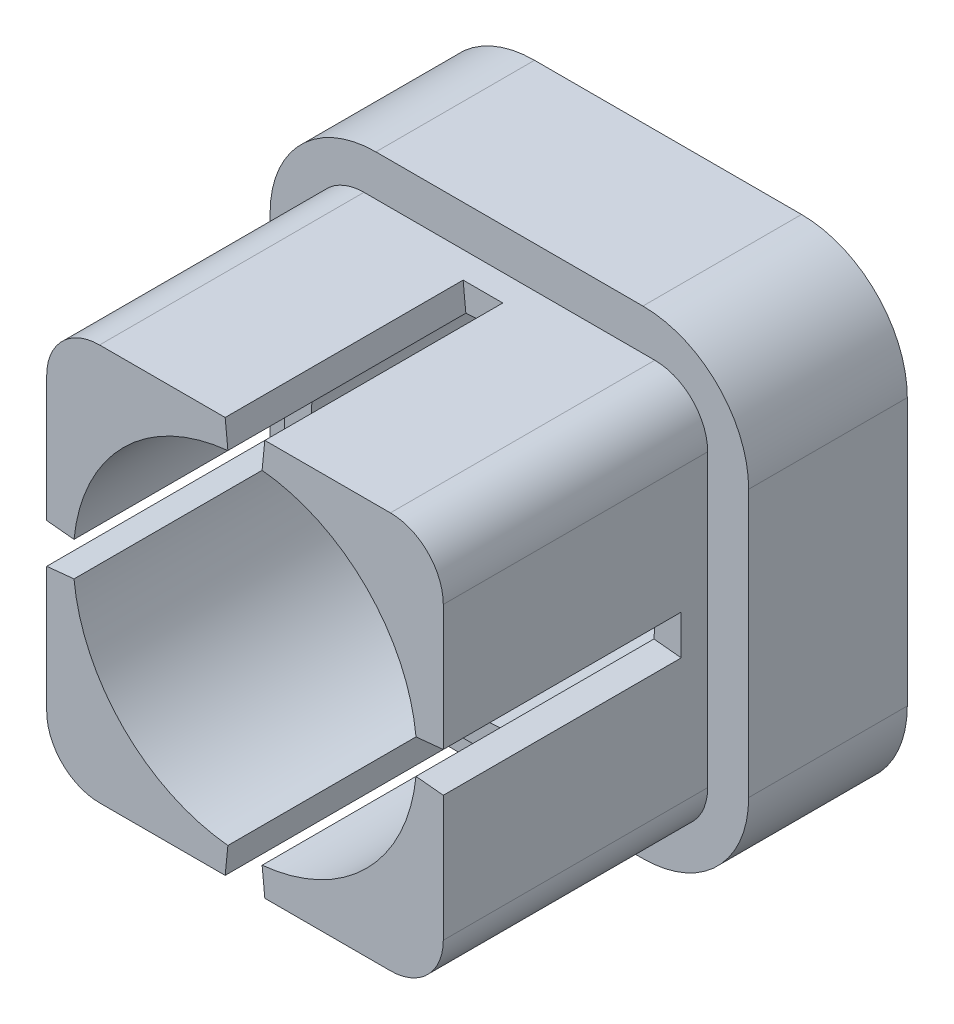
SolidWorks part; units mm, degrees
ref_plane "Front Plane" through (0, 0, 0) normal (0, 0, 1) x (1, 0, 0)
ref_plane "Top Plane" through (0, 0, 0) normal (0, 1, 0) x (1, 0, 0)
ref_plane "Right Plane" through (0, 0, 0) normal (1, 0, 0) x (0, 0, -1)
sketch "Sketch1" plane through (0, 0, 0) normal (0, 0, 1) x (1, 0, 0)
  line L0 (-5.05, 9.05) -> (5.05, 9.05)
  line L1 (9.05, -5.05) -> (9.05, 5.05)
  line L2 (0, 0) -> (0, 13.2587) construction
  line L3 (-9.05, -5.05) -> (-9.05, 5.05)
  line L4 (-13.9847, 0) -> (14.3758, 0) construction
  line L5 (-5.05, -9.05) -> (5.05, -9.05)
  arc A4 (5.05, 9.05) -> (9.05, 5.05) centre (5.05, 5.05) cw
  arc A5 (9.05, -5.05) -> (5.05, -9.05) centre (5.05, -5.05) cw
  arc A6 (-5.05, -9.05) -> (-9.05, -5.05) centre (-5.05, -5.05) cw
  arc A7 (-9.05, 5.05) -> (-5.05, 9.05) centre (-5.05, 5.05) cw
  point P11 (9.05, 0)
  point P12 (0, 9.05)
  point P20 (0, -9.05)
  point P21 (-9.05, 0)
  dimension "D3" = 0
  dimension "D1" = 5.05
  dimension "D2" = 5.05
  dimension "D4" = 9.05
  dimension "D5" = 9.05
extrude "Boss-Extrude1" add sketch "Sketch1" along normal blind 6
sketch "Sketch3" plane through (0, 0, 6) normal (0, 0, 1) x (1, 0, 0)
  line L1 (-5.5, -7.5) -> (5.5, -7.5)
  line L2 (-7.5, -5.5) -> (-7.5, 5.5)
  line L3 (-5.5, 7.5) -> (5.5, 7.5)
  line L4 (7.5, -5.5) -> (7.5, 5.5)
  line L5 (-7.5, -7.5) -> (7.5, 7.5) construction
  line L6 (-7.5, 7.5) -> (7.5, -7.5) construction
  arc A1 (-5.5, -7.5) -> (-7.5, -5.5) centre (-5.5, -5.5) cw
  arc A2 (5.5, -7.5) -> (7.5, -5.5) centre (5.5, -5.5) ccw
  arc A3 (5.5, 7.5) -> (7.5, 5.5) centre (5.5, 5.5) cw
  arc A4 (-7.5, 5.5) -> (-5.5, 7.5) centre (-5.5, 5.5) cw
  circle A5 centre (0, 0) radius 6.5
  point P2 (0, 0)
  dimension "D1" = 13
  dimension "D2" = 15
  dimension "D3" = 2
  dimension "D4" = 0
extrude "Boss-Extrude2" add sketch "Sketch3" along normal blind 10
sketch "Sketch4" plane through (0, 0, 16) normal (0, 0, 1) x (1, 0, 0)
  line L0 (0, 0) -> (7.5, 0.75)
  line L1 (7.5, -5.5) -> (7.5, 5.5) construction
  line L2 (7.5, 0.75) -> (7.5, -0.75)
  line L3 (7.5, -5.5) -> (7.5, 5.5) construction
  line L4 (0, 0) -> (7.5, -0.75)
  dimension "D1" = 0.75
  dimension "D2" = 0.75
extrude "Cut-Extrude1" cut sketch "Sketch4" against normal blind 9
pattern_circular "CirPattern1" count 4 every 90 about axis through (0, 0, 16) along (0, 0, -1) of "Cut-Extrude1"
sketch "Sketch5" plane through (0, 0, 0) normal (0, 0, 1) x (1, 0, 0)
  circle A0 centre (0, 0) radius 6.5
  dimension "D1" = 13
extrude "Cut-Extrude2" cut sketch "Sketch5" against normal mid plane 60
